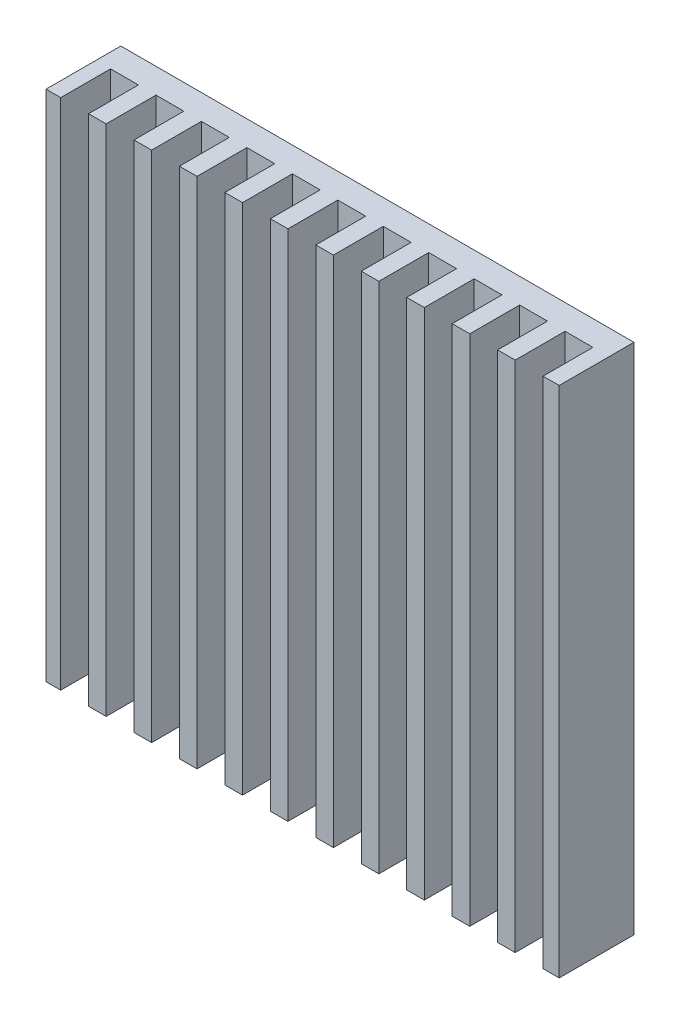
SolidWorks part; units mm, degrees
ref_plane "前视基准面" through (0, 0, 0) normal (0, 0, 1) x (1, 0, 0)
ref_plane "上视基准面" through (0, 0, 0) normal (0, 1, 0) x (1, 0, 0)
ref_plane "右视基准面" through (0, 0, 0) normal (1, 0, 0) x (0, 0, -1)
other "Configuration Table"
sketch "草图1" plane through (0, 0, 0) normal (0, 0, 1) x (1, 0, 0)
  line L1 (0, 0) -> (35, 0)
  line L2 (0, 0) -> (0, -35)
  line L3 (0, -35) -> (35, -35)
  line L4 (35, 0) -> (35, -35)
  dimension "D1" = 35
  dimension "D2" = 35
extrude "凸台-拉伸1" add sketch "草图1" along normal blind 5.1
sketch "草图2" plane through (0, -35, 0) normal (0, -1, 0) x (1, 0, 0)
  line L0 (0, 5.1) -> (35, 5.1) construction
  line L1 (1, 5.1) -> (2.9, 5.1)
  line L2 (1, 5.1) -> (1, 1.7)
  line L3 (1, 1.7) -> (2.9, 1.7)
  line L4 (2.9, 5.1) -> (2.9, 1.7)
  line L5 (0, 5.1) -> (0, 0) construction
  line L6 (4.1, 5.1) -> (4.1, 1.7)
  line L7 (4.1, 5.1) -> (6, 5.1)
  line L8 (6, 5.1) -> (6, 1.7)
  line L9 (4.1, 1.7) -> (6, 1.7)
  line L10 (7.2, 5.1) -> (7.2, 1.7)
  line L11 (7.2, 5.1) -> (9.1, 5.1)
  line L12 (9.1, 5.1) -> (9.1, 1.7)
  line L13 (7.2, 1.7) -> (9.1, 1.7)
  line L14 (10.3, 5.1) -> (10.3, 1.7)
  line L15 (10.3, 5.1) -> (12.2, 5.1)
  line L16 (12.2, 5.1) -> (12.2, 1.7)
  line L17 (10.3, 1.7) -> (12.2, 1.7)
  line L18 (13.4, 5.1) -> (13.4, 1.7)
  line L19 (13.4, 5.1) -> (15.3, 5.1)
  line L20 (15.3, 5.1) -> (15.3, 1.7)
  line L21 (13.4, 1.7) -> (15.3, 1.7)
  line L22 (16.5, 5.1) -> (16.5, 1.7)
  line L23 (16.5, 5.1) -> (18.4, 5.1)
  line L24 (18.4, 5.1) -> (18.4, 1.7)
  line L25 (16.5, 1.7) -> (18.4, 1.7)
  line L26 (19.6, 5.1) -> (19.6, 1.7)
  line L27 (19.6, 5.1) -> (21.5, 5.1)
  line L28 (21.5, 5.1) -> (21.5, 1.7)
  line L29 (19.6, 1.7) -> (21.5, 1.7)
  line L30 (22.7, 5.1) -> (22.7, 1.7)
  line L31 (22.7, 5.1) -> (24.6, 5.1)
  line L32 (24.6, 5.1) -> (24.6, 1.7)
  line L33 (22.7, 1.7) -> (24.6, 1.7)
  line L34 (25.8, 5.1) -> (25.8, 1.7)
  line L35 (25.8, 5.1) -> (27.7, 5.1)
  line L36 (27.7, 5.1) -> (27.7, 1.7)
  line L37 (25.8, 1.7) -> (27.7, 1.7)
  line L38 (28.9, 5.1) -> (28.9, 1.7)
  line L39 (28.9, 5.1) -> (30.8, 5.1)
  line L40 (30.8, 5.1) -> (30.8, 1.7)
  line L41 (28.9, 1.7) -> (30.8, 1.7)
  line L42 (32, 5.1) -> (32, 1.7)
  line L43 (32, 5.1) -> (33.9, 5.1)
  line L44 (33.9, 5.1) -> (33.9, 1.7)
  line L45 (32, 1.7) -> (33.9, 1.7)
  dimension "D1" = 1
  dimension "D2" = 3.4
  dimension "D3" = 1.9
  dimension "D4" = 11
extrude "切除-拉伸1" cut sketch "草图2" against normal through all
